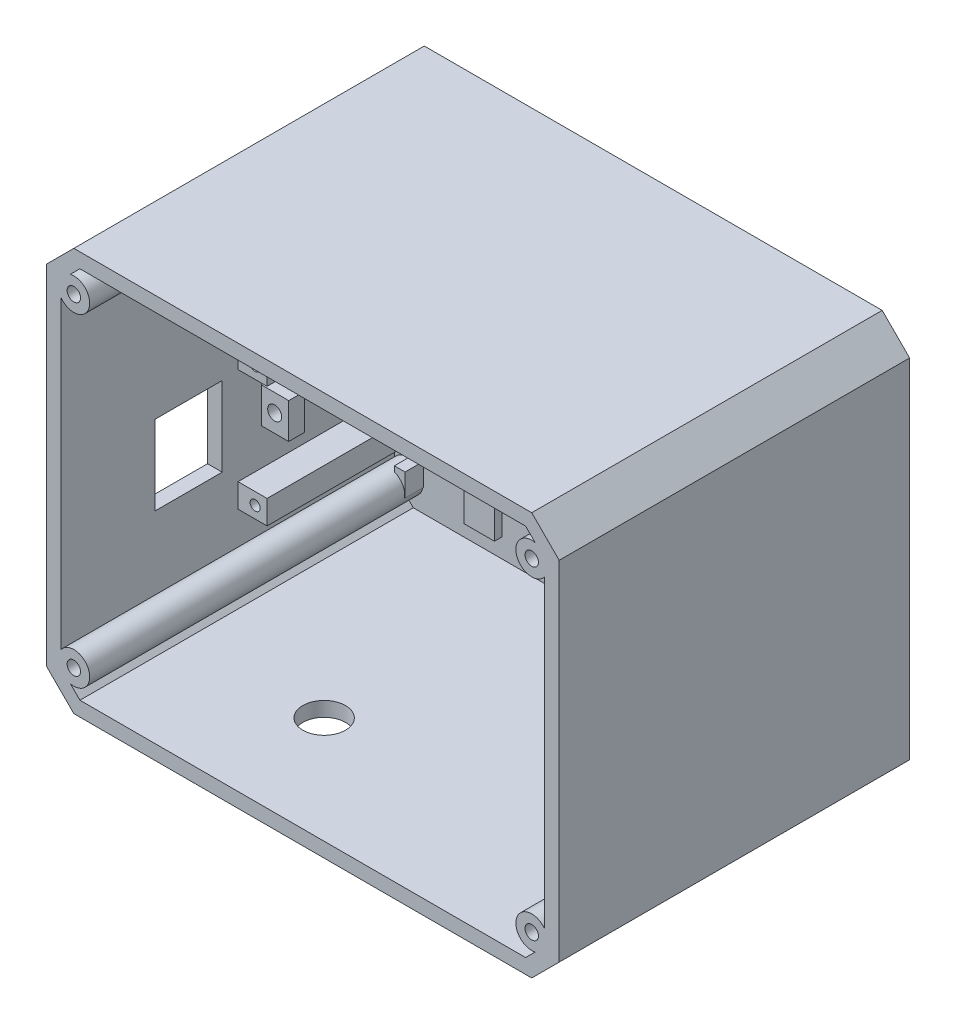
SolidWorks part; units mm, degrees
ref_plane "前视基准面" through (0, 0, 0) normal (0, 0, 1) x (1, 0, 0)
ref_plane "上视基准面" through (0, 0, 0) normal (0, 1, 0) x (1, 0, 0)
ref_plane "右视基准面" through (0, 0, 0) normal (1, 0, 0) x (0, 0, -1)
other "Configuration Table"
sketch "84 x 66 floor with case screw and battery strap holes profile" plane through (0, 0, 0) normal (0, 0, 1) x (1, 0, 0)
  line L0 (-37.5, -33) -> (37.5, -33)
  line L1 (37.5, -33) -> (42, -28.5)
  line L2 (42, -28.5) -> (42, 28.5)
  line L3 (42, 28.5) -> (37.5, 33)
  line L4 (37.5, 33) -> (-37.5, 33)
  line L5 (-37.5, 33) -> (-42, 28.5)
  line L6 (-42, 28.5) -> (-42, -28.5)
  line L7 (-42, -28.5) -> (-37.5, -33)
  line L8 (-0.3, -30.55) -> (5.3, -30.55)
  line L9 (5.3, -29.15) -> (-0.3, -29.15)
  line L10 (-0.1, 4.9) -> (5.1, 4.9)
  line L11 (5.1, 6.7) -> (-0.1, 6.7)
  circle A0 centre (-37.2, -9) radius 2.1
  circle A1 centre (37.2, -9) radius 2.1
  circle A2 centre (-37.2, 17) radius 2.1
  circle A3 centre (37.2, 17) radius 2.1
  arc A4 (5.3, -30.55) -> (5.3, -29.15) centre (5.3, -29.85) ccw
  arc A5 (-0.3, -29.15) -> (-0.3, -30.55) centre (-0.3, -29.85) ccw
  arc A6 (5.1, 4.9) -> (5.1, 6.7) centre (5.1, 5.8) ccw
  arc A7 (-0.1, 6.7) -> (-0.1, 4.9) centre (-0.1, 5.8) ccw
extrude "84 x 66 floor with case screw and battery strap holes" add sketch "84 x 66 floor with case screw and battery strap holes profile" along normal blind 2.8
sketch "2.4 mm perimeter wall profile" plane through (0, 0, 0) normal (0, 0, 1) x (1, 0, 0)
  line L0 (-37.5, -33) -> (37.5, -33)
  line L1 (37.5, -33) -> (42, -28.5)
  line L2 (42, -28.5) -> (42, 28.5)
  line L3 (42, 28.5) -> (37.5, 33)
  line L4 (37.5, 33) -> (-37.5, 33)
  line L5 (-37.5, 33) -> (-42, 28.5)
  line L6 (-42, 28.5) -> (-42, -28.5)
  line L7 (-42, -28.5) -> (-37.5, -33)
  line L8 (-36.5, -30.6) -> (36.5, -30.6)
  line L9 (36.5, -30.6) -> (39.6, -27.5)
  line L10 (39.6, -27.5) -> (39.6, 27.5)
  line L11 (39.6, 27.5) -> (36.5, 30.6)
  line L12 (36.5, 30.6) -> (-36.5, 30.6)
  line L13 (-36.5, 30.6) -> (-39.6, 27.5)
  line L14 (-39.6, 27.5) -> (-39.6, -27.5)
  line L15 (-39.6, -27.5) -> (-36.5, -30.6)
extrude "2.4 mm perimeter wall" add sketch "2.4 mm perimeter wall profile" along normal blind 54.6 from offset 2.8
sketch "Lid D2.2 pilots core profile" plane through (0, 0, 0) normal (0, 0, 1) x (1, 0, 0)
  circle A0 centre (-37.5, -26.5) radius 2.6
  circle A1 centre (37.5, -26.5) radius 2.6
  circle A2 centre (-37.5, 26.5) radius 2.6
  circle A3 centre (37.5, 26.5) radius 2.6
extrude "Lid D2.2 pilots core" add sketch "Lid D2.2 pilots core profile" along normal blind 46.6 from offset 2.8
sketch "Lid D2.2 pilots profile" plane through (0, 0, 0) normal (0, 0, 1) x (1, 0, 0)
  circle A0 centre (-37.5, -26.5) radius 2.6
  circle A1 centre (37.5, -26.5) radius 2.6
  circle A2 centre (-37.5, 26.5) radius 2.6
  circle A3 centre (37.5, 26.5) radius 2.6
  circle A4 centre (-37.5, -26.5) radius 1.1
  circle A5 centre (37.5, -26.5) radius 1.1
  circle A6 centre (-37.5, 26.5) radius 1.1
  circle A7 centre (37.5, 26.5) radius 1.1
extrude "Lid D2.2 pilots" add sketch "Lid D2.2 pilots profile" along normal blind 8 from offset 49.4
sketch "Wall-backed shelf support ribs profile" plane through (0, 0, 0) normal (0, 0, 1) x (1, 0, 0)
  line L0 (34.85, -19.55) -> (40, -19.55)
  line L1 (40, -19.55) -> (40, -15.65)
  line L2 (40, -15.65) -> (34.85, -15.65)
  line L3 (34.85, -15.65) -> (34.85, -19.55)
  line L4 (-40, -19.55) -> (-34.85, -19.55)
  line L5 (-34.85, -19.55) -> (-34.85, -15.65)
  line L6 (-34.85, -15.65) -> (-40, -15.65)
  line L7 (-40, -15.65) -> (-40, -19.55)
  line L8 (34.85, 0.25) -> (40, 0.25)
  line L9 (40, 0.25) -> (40, 4.15)
  line L10 (40, 4.15) -> (34.85, 4.15)
  line L11 (34.85, 4.15) -> (34.85, 0.25)
  line L12 (-40, 0.25) -> (-34.85, 0.25)
  line L13 (-34.85, 0.25) -> (-34.85, 4.15)
  line L14 (-34.85, 4.15) -> (-40, 4.15)
  line L15 (-40, 4.15) -> (-40, 0.25)
extrude "Wall-backed shelf support ribs" add sketch "Wall-backed shelf support ribs profile" along normal blind 19.6 from offset 2.8
sketch "Wall-backed shelf support D1.65 pilots profile" plane through (0, 0, 0) normal (0, 0, 1) x (1, 0, 0)
  line L0 (34.85, -19.55) -> (40, -19.55)
  line L1 (40, -19.55) -> (40, -15.65)
  line L2 (40, -15.65) -> (34.85, -15.65)
  line L3 (34.85, -15.65) -> (34.85, -19.55)
  line L4 (-40, -19.55) -> (-34.85, -19.55)
  line L5 (-34.85, -19.55) -> (-34.85, -15.65)
  line L6 (-34.85, -15.65) -> (-40, -15.65)
  line L7 (-40, -15.65) -> (-40, -19.55)
  line L8 (34.85, 0.25) -> (40, 0.25)
  line L9 (40, 0.25) -> (40, 4.15)
  line L10 (40, 4.15) -> (34.85, 4.15)
  line L11 (34.85, 4.15) -> (34.85, 0.25)
  line L12 (-40, 0.25) -> (-34.85, 0.25)
  line L13 (-34.85, 0.25) -> (-34.85, 4.15)
  line L14 (-34.85, 4.15) -> (-40, 4.15)
  line L15 (-40, 4.15) -> (-40, 0.25)
  circle A0 centre (-36.8, -17.6) radius 0.825
  circle A1 centre (36.8, -17.6) radius 0.825
  circle A2 centre (-36.8, 2.2) radius 0.825
  circle A3 centre (36.8, 2.2) radius 0.825
extrude "Wall-backed shelf support D1.65 pilots" add sketch "Wall-backed shelf support D1.65 pilots profile" along normal blind 6 from offset 22.4
sketch "Sensor D1.65 pilots - 19 mm centers profile" plane through (0, 0, 0) normal (0, 0, 1) x (1, 0, 0)
  circle A0 centre (7, 27) radius 2.8
  circle A1 centre (26, 27) radius 2.8
  circle A2 centre (7, 27) radius 0.825
  circle A3 centre (26, 27) radius 0.825
extrude "Sensor D1.65 pilots - 19 mm centers" add sketch "Sensor D1.65 pilots - 19 mm centers profile" along normal blind 3.6 from offset 2.8
sketch "GNSS M2 D1.65 pilots - centers provisional profile" plane through (0, 0, 0) normal (0, 0, 1) x (1, 0, 0)
  circle A0 centre (-29.05, 7) radius 2.65
  circle A1 centre (-29.05, 27.8) radius 2.65
  circle A2 centre (-29.05, 7) radius 0.825
  circle A3 centre (-29.05, 27.8) radius 0.825
extrude "GNSS M2 D1.65 pilots - centers provisional" add sketch "GNSS M2 D1.65 pilots - centers provisional profile" along normal blind 3.6 from offset 2.8
sketch "GNSS plain support profile" plane through (0, 0, 0) normal (0, 0, 1) x (1, 0, 0)
  line L0 (-5.6, 22.3) -> (-1.7, 22.3)
  line L1 (-1.7, 22.3) -> (-1.7, 27)
  line L2 (-1.7, 27) -> (-5.6, 27)
  line L3 (-5.6, 27) -> (-5.6, 22.3)
extrude "GNSS plain support" add sketch "GNSS plain support profile" along normal blind 3.6 from offset 2.8
sketch "Battery end stops profile" plane through (0, 0, 0) normal (0, 0, 1) x (1, 0, 0)
  line L0 (-36.6, -26.9) -> (-34.85, -26.9)
  line L1 (-34.85, -26.9) -> (-34.85, -23.2)
  line L2 (-34.85, -23.2) -> (-36.6, -23.2)
  line L3 (-36.6, -23.2) -> (-36.6, -26.9)
  line L4 (34.85, -27.1) -> (36.6, -27.1)
  line L5 (36.6, -27.1) -> (36.6, -23.2)
  line L6 (36.6, -23.2) -> (34.85, -23.2)
  line L7 (34.85, -23.2) -> (34.85, -27.1)
extrude "Battery end stops" add sketch "Battery end stops profile" along normal blind 3 from offset 2.8
sketch "Battery supports with strap space below profile" plane through (0, 0, 0) normal (0, 0, 1) x (1, 0, 0)
  line L0 (-27, -27.5) -> (-22, -27.5)
  line L1 (-22, -27.5) -> (-22, 2)
  line L2 (-22, 2) -> (-27, 2)
  line L3 (-27, 2) -> (-27, -27.5)
  line L4 (22, -27.5) -> (27, -27.5)
  line L5 (27, -27.5) -> (27, 2)
  line L6 (27, 2) -> (22, 2)
  line L7 (22, 2) -> (22, -27.5)
extrude "Battery supports with strap space below" add sketch "Battery supports with strap space below profile" along normal blind 1.2 from offset 2.8
sketch "Power plate raised guide seats profile" plane through (0, 0, 0) normal (0, 0, 1) x (1, 0, 0)
  line L0 (-36.2, 25.8) -> (-30.1, 25.8)
  line L1 (-30.1, 25.8) -> (-30.1, 31.1)
  line L2 (-30.1, 31.1) -> (-36.2, 31.1)
  line L3 (-36.2, 31.1) -> (-36.2, 25.8)
  line L4 (30.1, 25.8) -> (36.2, 25.8)
  line L5 (36.2, 25.8) -> (36.2, 31.1)
  line L6 (36.2, 31.1) -> (30.1, 31.1)
  line L7 (30.1, 31.1) -> (30.1, 25.8)
extrude "Power plate raised guide seats" add sketch "Power plate raised guide seats profile" along normal blind 2.4 from offset 18.2
sketch "Power plate raised guide channels profile" plane through (0, 0, 0) normal (0, 0, 1) x (1, 0, 0)
  line L0 (-30.1, 25.8) -> (-36.2, 25.8)
  line L1 (-36.2, 25.8) -> (-36.2, 31.1)
  line L2 (-36.2, 31.1) -> (-32.4, 31.1)
  line L3 (-32.4, 31.1) -> (-32.4, 26.75)
  line L4 (-32.4, 26.75) -> (-30.1, 26.75)
  line L5 (-30.1, 26.75) -> (-30.1, 25.8)
  line L6 (30.1, 25.8) -> (36.2, 25.8)
  line L7 (36.2, 25.8) -> (36.2, 31.1)
  line L8 (36.2, 31.1) -> (32.4, 31.1)
  line L9 (32.4, 31.1) -> (32.4, 26.75)
  line L10 (32.4, 26.75) -> (30.1, 26.75)
  line L11 (30.1, 26.75) -> (30.1, 25.8)
extrude "Power plate raised guide channels" add sketch "Power plate raised guide channels profile" along normal blind 18.3 from offset 20.6
sketch "Power keeper washer D2.1 pilots profile" plane through (0, 0, 0) normal (0, 0, 1) x (1, 0, 0)
  line L0 (-30.1, 25.8) -> (-36.2, 25.8)
  line L1 (-36.2, 25.8) -> (-36.2, 31.1)
  line L2 (-36.2, 31.1) -> (-32.4, 31.1)
  line L3 (-32.4, 31.1) -> (-32.4, 26.75)
  line L4 (-32.4, 26.75) -> (-30.1, 26.75)
  line L5 (-30.1, 26.75) -> (-30.1, 25.8)
  line L6 (30.1, 25.8) -> (36.2, 25.8)
  line L7 (36.2, 25.8) -> (36.2, 31.1)
  line L8 (36.2, 31.1) -> (32.4, 31.1)
  line L9 (32.4, 31.1) -> (32.4, 26.75)
  line L10 (32.4, 26.75) -> (30.1, 26.75)
  line L11 (30.1, 26.75) -> (30.1, 25.8)
  circle A0 centre (-34.1, 28.4) radius 1.05
  circle A1 centre (34.1, 28.4) radius 1.05
extrude "Power keeper washer D2.1 pilots" add sketch "Power keeper washer D2.1 pilots profile" along normal blind 4.5 from offset 38.9
sketch "Wall wiring tie eye at 11 profile" plane through (0, 0, 0) normal (0, 0, 1) x (1, 0, 0)
  line L0 (-39.8, -9.6) -> (-35.1, -9.6)
  line L1 (-35.1, -9.6) -> (-35.1, -3.8)
  line L2 (-35.1, -3.8) -> (-39.8, -3.8)
  line L3 (-39.8, -3.8) -> (-39.8, -9.6)
  circle A0 centre (-37.4, -6.7) radius 1.15
extrude "Wall wiring tie eye at 11" add sketch "Wall wiring tie eye at 11 profile" along normal blind 2.6 from offset 11
sketch "Wall wiring tie eye at 22 profile" plane through (0, 0, 0) normal (0, 0, 1) x (1, 0, 0)
  line L0 (-39.8, -9.6) -> (-35.1, -9.6)
  line L1 (-35.1, -9.6) -> (-35.1, -3.8)
  line L2 (-35.1, -3.8) -> (-39.8, -3.8)
  line L3 (-39.8, -3.8) -> (-39.8, -9.6)
  circle A0 centre (-37.4, -6.7) radius 1.15
extrude "Wall wiring tie eye at 22" add sketch "Wall wiring tie eye at 22 profile" along normal blind 2.6 from offset 22
sketch "USB reserve 13 x 11 at lower end of PCB profile" plane through (0, 0, 0) normal (0, 0, 1) x (1, 0, 0)
  line L0 (-42.4, -13) -> (-39, -13)
  line L1 (-39, -13) -> (-39, 0)
  line L2 (-39, 0) -> (-42.4, 0)
  line L3 (-42.4, 0) -> (-42.4, -13)
extrude "USB reserve 13 x 11 at lower end of PCB" cut sketch "USB reserve 13 x 11 at lower end of PCB profile" against normal blind 11 from offset 42
sketch "D7 round port for D6.5 antenna - 18 from PCB bottom profile" plane through (0, -33, 0) normal (0, -1, 0) x (1, 0, 0)
  circle A0 centre (-14, 39.9) radius 3.5
extrude "D7 round port for D6.5 antenna - 18 from PCB bottom" cut sketch "D7 round port for D6.5 antenna - 18 from PCB bottom profile" against normal blind 2.5
